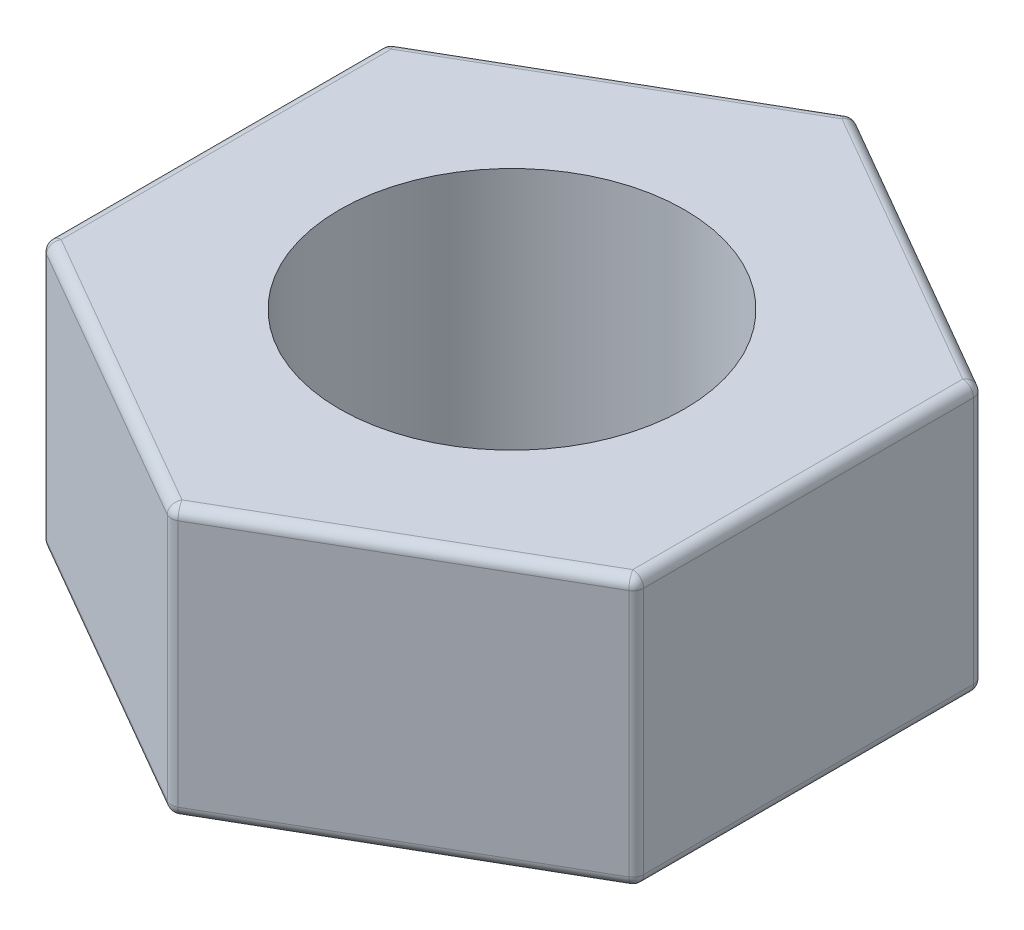
SolidWorks part; units mm, degrees
material "Plain Carbon Steel"
ref_plane "Front Plane" through (0, 0, 0) normal (0, 0, 1) x (1, 0, 0)
ref_plane "Top Plane" through (0, 0, 0) normal (0, 1, 0) x (1, 0, 0)
ref_plane "Right Plane" through (0, 0, 0) normal (1, 0, 0) x (0, 0, -1)
sketch "Sketch1" plane through (0, 0, 0) normal (0, 1, 0) x (1, 0, 0)
  line L1 (0, 3.1754) -> (-2.75, 1.5877)
  line L2 (-2.75, 1.5877) -> (-2.75, -1.5877)
  line L3 (-2.75, -1.5877) -> (0, -3.1754)
  line L4 (0, -3.1754) -> (2.75, -1.5877)
  line L5 (2.75, -1.5877) -> (2.75, 1.5877)
  line L6 (2.75, 1.5877) -> (0, 3.1754)
  circle A0 centre (0, 0) radius 2.75 construction
  circle A1 centre (0, 0) radius 1.6
  dimension "D2" = 3.2
  dimension "D1" = 5.5
extrude "Boss-Extrude1" add sketch "Sketch1" along normal blind 2.5
fillet "Fillet1" radius 0.1 18 edges at (1.375, 2.5, -2.3816) (1.375, 0, -2.3816) (0, 1.25, -3.1754) (-1.375, 2.5, -2.3816) (-1.375, 0, -2.3816) (-2.75, 1.25, -1.5877) (-2.75, 2.5, 0) (-2.75, 0, 0) (-2.75, 1.25, 1.5877) (-1.375, 2.5, 2.3816) (-1.375, 0, 2.3816) (2.75, 2.5, 0) (2.75, 1.25, -1.5877) (2.75, 0, 0) (0, 1.25, 3.1754) (1.375, 2.5, 2.3816) (2.75, 1.25, 1.5877) (1.375, 0, 2.3816)
